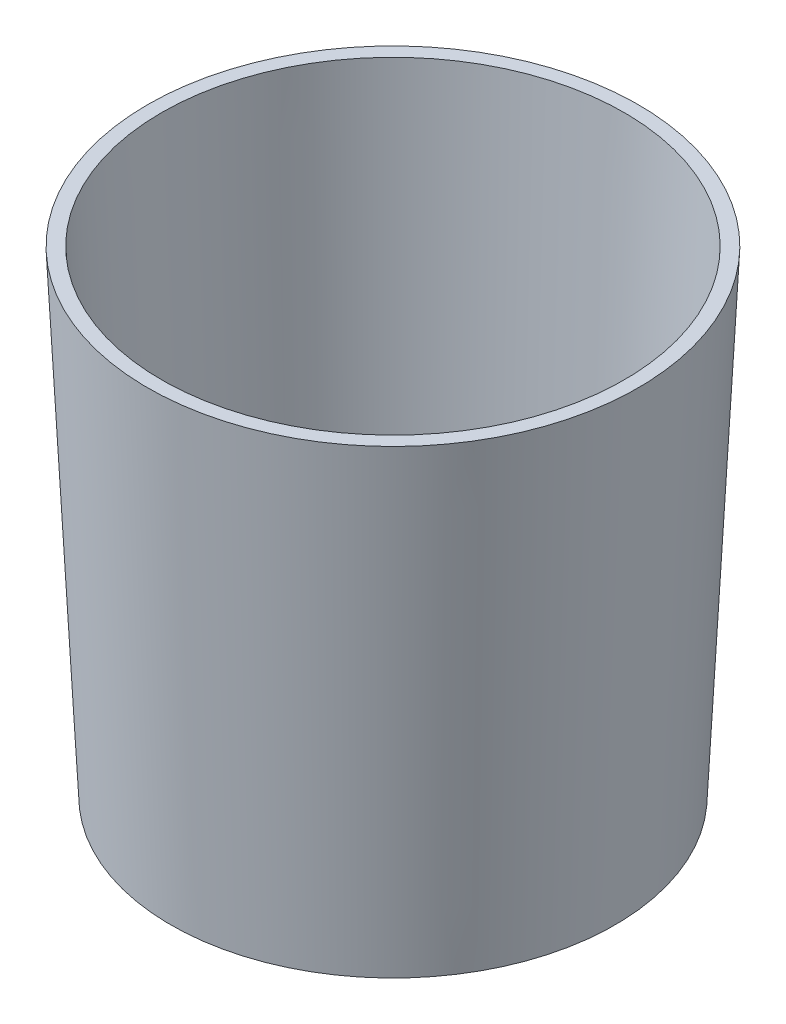
SolidWorks part; units mm, degrees
ref_plane "Front Plane" through (0, 0, 0) normal (0, 0, 1) x (1, 0, 0)
ref_plane "Top Plane" through (0, 0, 0) normal (0, 1, 0) x (1, 0, 0)
ref_plane "Right Plane" through (0, 0, 0) normal (1, 0, 0) x (0, 0, -1)
sketch "Sketch1" plane through (0, 0, 0) normal (0, 0, 1) x (1, 0, 0)
  line L0 (0, 36.75) -> (0, -66.25)
  line L1 (0, -66.25) -> (48, -66.25)
  line L2 (48, -66.25) -> (53, 36.75)
  line L3 (53, 36.75) -> (0, 36.75)
  dimension "D1" = 53
  dimension "D2" = 48
  dimension "D3" = 103
revolve "Revolve1" add sketch "Sketch1" angle 360 about L0
sketch "Sketch3" plane through (0, 36.75, 0) normal (0, 1, 0) x (1, 0, 0)
  circle A0 centre (0, 0) radius 50
extrude "Cut-Extrude1" cut sketch "Sketch3" against normal blind 100 draft 2.6
